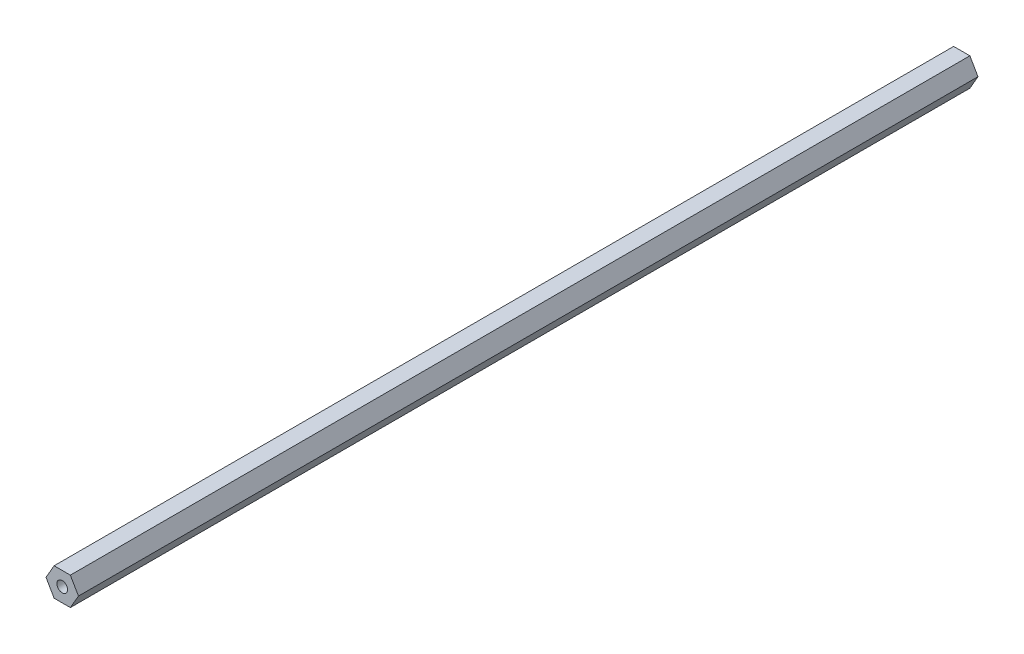
SolidWorks part; units mm, degrees
ref_plane "Front Plane" through (0, 0, 0) normal (0, 0, 1) x (1, 0, 0)
ref_plane "Top Plane" through (0, 0, 0) normal (0, 1, 0) x (1, 0, 0)
ref_plane "Right Plane" through (0, 0, 0) normal (1, 0, 0) x (0, 0, -1)
sketch "Sketch1" plane through (0, 0, 0) normal (0, 0, 1) x (1, 0, 0)
  line L1 (7.3323, 0) -> (3.6662, 6.35)
  line L2 (3.6662, 6.35) -> (-3.6662, 6.35)
  line L3 (-3.6662, 6.35) -> (-7.3323, 0)
  line L4 (-7.3323, 0) -> (-3.6662, -6.35)
  line L5 (-3.6662, -6.35) -> (3.6662, -6.35)
  line L6 (3.6662, -6.35) -> (7.3323, 0)
  circle A0 centre (0, 0) radius 6.35 construction
  dimension "D1" = 12.7
extrude "Boss-Extrude1" add sketch "Sketch1" along normal blind 406.4
sketch "Sketch2" plane through (0, 0, 406.4) normal (0, 0, 1) x (1, 0, 0)
  circle A0 centre (0, 0) radius 2.413
  dimension "D1" = 4.826
extrude "Cut-Extrude1" cut sketch "Sketch2" against normal through all both and the other way through all
